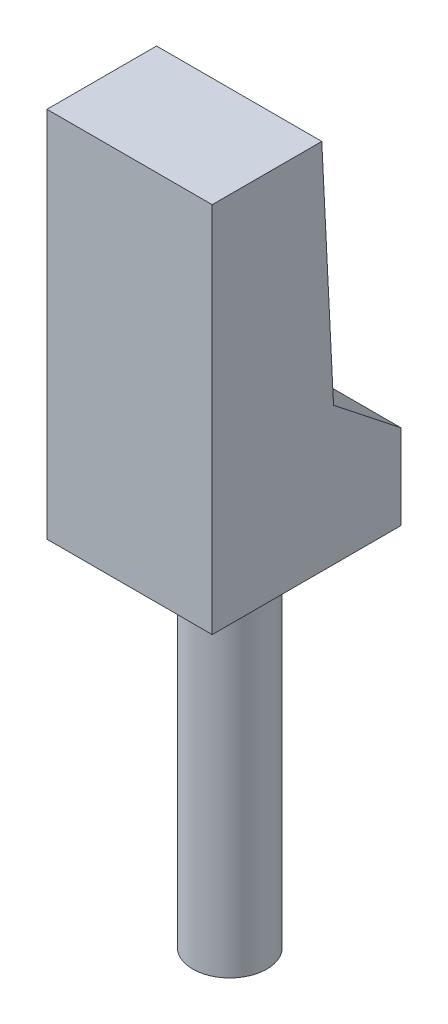
SolidWorks part; units mm, degrees
ref_plane "Front Plane" through (0, 0, 0) normal (0, 0, 1) x (1, 0, 0)
ref_plane "Top Plane" through (0, 0, 0) normal (0, 1, 0) x (1, 0, 0)
ref_plane "Right Plane" through (0, 0, 0) normal (1, 0, 0) x (0, 0, -1)
sketch "Sketch1" plane through (0, 0, 0) normal (0, 1, 0) x (1, 0, 0)
  line L1 (0, 0) -> (-17.7514, 0)
  line L2 (0, 0) -> (0, 20.2894)
  line L3 (0, 20.2894) -> (-17.7514, 20.2894)
  line L4 (-17.7514, 0) -> (-17.7514, 20.2894)
extrude "Boss-Extrude1" add sketch "Sketch1" along normal blind 40
sketch "Sketch2" plane through (0, 0, 0) normal (0, -1, 0) x (-1, 0, 0)
  circle A0 centre (8.636, 10.5304) radius 3.9808
sketch3d "3DSketch1"
  line L0 (-8.636, 0, -10.5304) -> (-8.636, -38.7165, -10.5304)
sweep "Sweep1" add profiles "Sketch2" path "3DSketch1"
sketch "Sketch3" plane through (0, 0, 0) normal (1, 0, 0) x (0, 0, -1)
  line L0 (27.3318, 3.5266) -> (13.0367, 14.8267)
  line L1 (13.0367, 14.8267) -> (11.5492, 44.4741)
  line L2 (11.5492, 44.4741) -> (29.8028, 42.7214)
  line L3 (29.8028, 42.7214) -> (27.3318, 3.5266)
extrude "Cut-Extrude1" cut sketch "Sketch3" against normal blind 40
